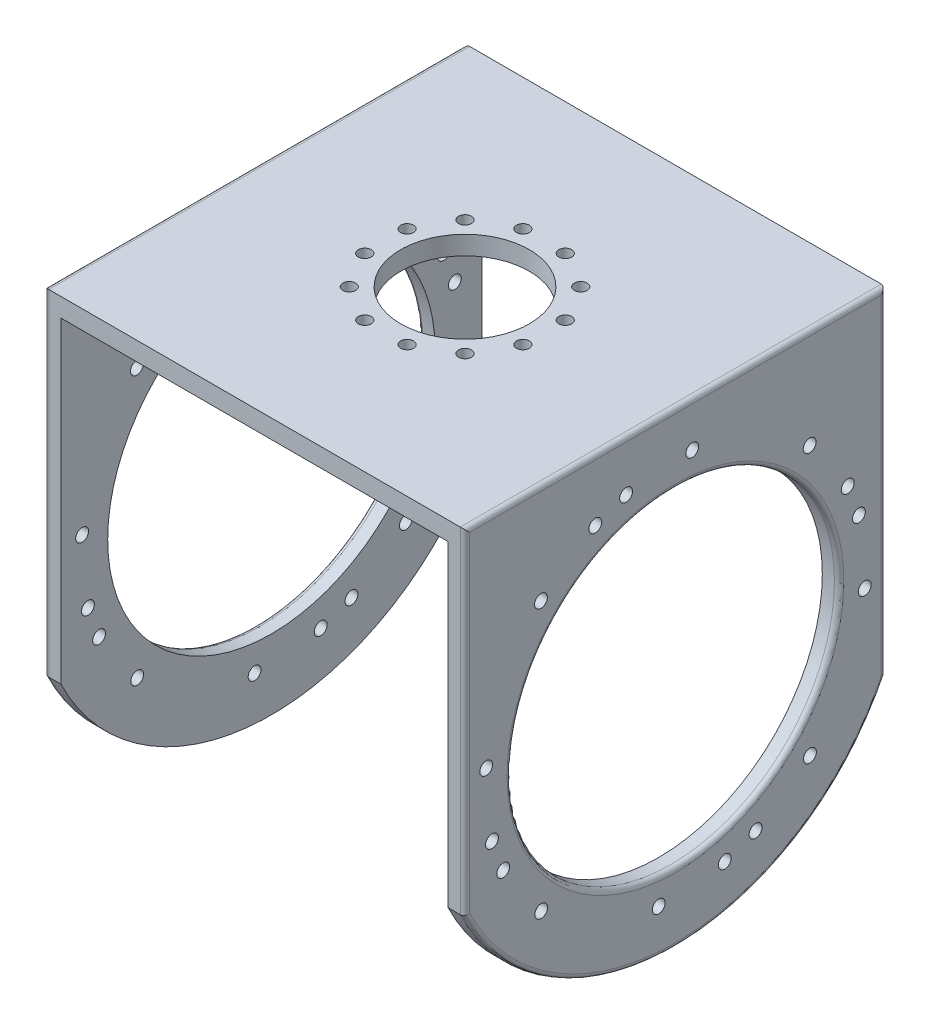
SolidWorks part; units mm, degrees
material "6061 合金"
ref_plane "前视基准面" through (0, 0, 0) normal (0, 0, 1) x (1, 0, 0)
ref_plane "上视基准面" through (0, 0, 0) normal (0, 1, 0) x (1, 0, 0)
ref_plane "右视基准面" through (0, 0, 0) normal (1, 0, 0) x (0, 0, -1)
other "Configuration Table"
sketch "草图1" plane through (0, 0, 0) normal (0, 0, 1) x (1, 0, 0)
  line L0 (0, 0) -> (0, 218.3382) construction
  line L1 (-90, 200) -> (90, 200)
  line L2 (90, 200) -> (90, 0)
  line L3 (90, 0) -> (82.8, 0)
  line L4 (82.8, 0) -> (82.8, 192)
  line L5 (82.8, 192) -> (-82.8, 192)
  line L6 (-82.8, 0) -> (-82.8, 192)
  line L7 (-90, 0) -> (-82.8, 0)
  line L8 (-90, 200) -> (-90, 0)
  point P11 (0, 192)
  point P14 (0, 200)
  dimension "D1" = 8
  dimension "D2" = 7.2
  dimension "D3" = 200
  dimension "D4" = 90
extrude "凸台-拉伸1" add sketch "草图1" along normal blind 180
sketch "草图2" plane through (0, 200, 0) normal (0, 1, 0) x (1, 0, 0)
  line L0 (-107.1953, -90) -> (124.7074, -90) construction
  line L1 (0, 14.5236) -> (0, -191.0225) construction
  line L2 (90, 0) -> (-90, 0) construction
  line L3 (90, -180) -> (-90, -180) construction
  circle A0 centre (0, -90) radius 27.5
  dimension "D1" = 55
extrude "切除-拉伸1" cut sketch "草图2" against normal blind 180
sketch "草图3" plane through (90, 0, 0) normal (1, 0, 0) x (0, 0, -1)
  line L0 (-202.0275, 100) -> (22.0275, 100) construction
  line L1 (-90, 182.9754) -> (-90, -6.0566) construction
  line L2 (-180, 0) -> (0, 0) construction
  line L3 (-180, 200) -> (0, 200) construction
  line L4 (0, 0) -> (0, 200) construction
  line L5 (-180, 0) -> (-180, 200) construction
  circle A0 centre (-90, 100) radius 70
  dimension "D1" = 140
extrude "切除-拉伸2" cut sketch "草图3" against normal blind 217 contours A0
sketch "草图4" plane through (0, 0, 0) normal (1, 0, 0) x (0, 0, -1)
  line L0 (-90, 200) -> (-90, 143.0513) construction
  line L1 (-62.5, 200) -> (-117.5, 200) construction
  line L2 (-70, 430) -> (60, 66.6573)
  line L3 (60, 66.6573) -> (-90, 66.6573) construction
  line L4 (-90, 66.6573) -> (-90, 700) construction
  line L5 (-70, 700) -> (60, 700)
  line L6 (60, 700) -> (60, 66.6573)
  line L7 (-70, 700) -> (-70, 430)
  circle A0 centre (-90, 100) radius 70 construction
  dimension "D1" = 500
  dimension "D2" = 130
  dimension "D3" = 150
  dimension "D4" = 230
  dimension "D5" = 20
revolve "切除-旋转6" [suppressed] cut sketch "草图4" angle 360 about L4
sketch "草图6" [suppressed] plane through (0, 0, 0) normal (1, 0, 0) x (0, 0, -1)
  line L0 (15.1538, 192) -> (60, 66.6573)
  line L1 (-25.1812, 192) -> (0, 192) construction
  line L2 (60, 66.6573) -> (-90, 66.6573) construction
  line L3 (60, 66.6573) -> (51.5034, 66.6573)
  line L4 (51.5034, 66.6573) -> (6.6571, 192)
  line L5 (-70, 430) -> (60, 66.6573) construction
  line L6 (6.6571, 192) -> (15.1538, 192)
  line L7 (-90, 66.6573) -> (-90, 200) construction
  dimension "D1" = 8
revolve "旋转1" [suppressed] add sketch "草图6" angle 360 about L7
sketch "草图7" [suppressed] plane through (0, 0, 0) normal (0, 0, 1) x (1, 0, 0)
  line L0 (90, 0) -> (90, 200)
  line L1 (90, 200) -> (162.5084, 200)
  line L2 (162.5084, 200) -> (162.5084, -21.519)
  line L3 (162.5084, -21.519) -> (-191.6551, -21.519)
  line L4 (-191.6551, -21.519) -> (-191.6551, 200)
  line L5 (-191.6551, 200) -> (-90, 200)
  line L6 (-90, 200) -> (-90, 0)
  line L7 (-90, 0) -> (-82.8, 0)
  line L10 (-35.2505, 192) -> (35.2505, 192)
  line L12 (82.8, 0) -> (90, 0)
  line L14 (35.2505, 192) -> (-35.2505, 192) construction
  line L15 (82.8, 0) -> (82.8, 120.3462)
  line L16 (82.8, 120.3462) -> (35.2505, 192)
  line L17 (-82.8, 0) -> (-82.8, 120.3462)
  line L18 (-82.8, 120.3462) -> (-35.2505, 192)
  line L19 (0, 0) -> (0, 120.3462) construction
  line L21 (35.2505, 192) -> (82.8, 192) construction
  line L22 (-82.8, 0) -> (-82.8, 120.3462) construction
  line L23 (-141.5034, 66.6573) -> (141.5034, 66.6573) construction
  line L24 (-35.2505, 192) -> (35.2505, 192) construction
  dimension "D1" = 53.6889
  dimension "D2" = 35.2505
extrude "切除-拉伸3" [suppressed] cut sketch "草图7" against normal through all both and the other way through all
sketch "草图8" [suppressed] plane through (-90, 0, 0) normal (-1, 0, 0) x (0, 0, 1)
  line L0 (0, 0) -> (0, 200)
  line L1 (0, 200) -> (180, 200)
  line L2 (180, 200) -> (180, 0)
  line L3 (180, 106.4129) -> (180, 0) construction
  line L4 (180, 0) -> (231.7354, 0)
  line L5 (231.7354, 0) -> (231.7354, 213.4055)
  line L6 (231.7354, 213.4055) -> (-43.5189, 213.4055)
  line L7 (-43.5189, 213.4055) -> (-43.5189, 0)
  line L8 (-43.5189, 0) -> (0, 0)
extrude "切除-拉伸4" [suppressed] cut sketch "草图8" against normal through all both
sketch "草图9" plane through (90, 0, 0) normal (1, 0, 0) x (0, 0, -1)
  line L3 (0, 56.411) -> (0, 0)
  line L4 (-180, 200) -> (-180, 0)
  line L5 (-180, 0) -> (0, 0)
  line L6 (0, 0) -> (0, 200)
  line L7 (0, 200) -> (-180, 200)
  line L8 (-180, 56.411) -> (-180, 0)
  line L9 (-180, 0) -> (0, 0)
  line L11 (0, 200) -> (-180, 200) construction
  circle A0 centre (-90, 100) radius 70 construction
  circle A1 centre (-90, 100) radius 70 construction
  arc A3 (-180, 56.411) -> (0, 56.411) centre (-90, 100) ccw
  line M11 (-180, 200) -> (-180, 0)
  line M12 (-180, 0) -> (0, 0)
  line M13 (0, 0) -> (0, 200)
  dimension "D1" = 0
extrude "切除-拉伸5" cut sketch "草图9" against normal through all both contours A3 L9 M13 | A3 M11 M12
fillet "圆角1" [suppressed] radius 2
fillet "圆角2" radius 2 10 edges at (90, 200, 90) (90, 128.2055, 0) (90, 0, 90) (90, 128.2055, 180) (90, 170, 90) (-90, 128.2055, 0) (-90, 200, 90) (-90, 128.2055, 180) (-90, 0, 90) (-90, 170, 90)
sketch "草图10" plane through (90, 0, 0) normal (1, 0, 0) x (0, 0, -1)
  arc A0 (-173.1989, 108.2258) -> (-168.6673, 106.1128) centre (-170.9331, 107.1693) ccw construction
  arc A1 (-170.7244, 79.9423) -> (-166.1928, 77.8292) centre (-168.4586, 78.8857) ccw construction
  arc A2 (-165.9405, 66.7988) -> (-161.409, 64.6857) centre (-163.6748, 65.7423) ccw construction
  arc A3 (-149.6558, 43.5418) -> (-145.1242, 41.4287) centre (-147.39, 42.4852) ccw construction
  arc A4 (-99.4351, 20.1235) -> (-94.9035, 18.0104) centre (-97.1693, 19.0669) ccw construction
  arc A5 (-71.1515, 22.598) -> (-66.62, 20.4849) centre (-68.8857, 21.5414) ccw construction
  arc A6 (-58.008, 27.3818) -> (-53.4765, 25.2687) centre (-55.7423, 26.3252) ccw construction
  arc A7 (-34.751, 43.6665) -> (-30.2194, 41.5535) centre (-32.4852, 42.61) ccw construction
  arc A8 (-11.3327, 93.8872) -> (-6.8011, 91.7742) centre (-9.0669, 92.8307) ccw construction
  arc A9 (-13.8072, 122.1708) -> (-9.2756, 120.0577) centre (-11.5414, 121.1143) ccw construction
  arc A10 (-18.591, 135.3143) -> (-14.0595, 133.2012) centre (-16.3252, 134.2577) ccw construction
  arc A11 (-34.8758, 158.5713) -> (-30.3442, 156.4582) centre (-32.61, 157.5148) ccw construction
  arc A12 (-85.0965, 181.9896) -> (-80.5649, 179.8765) centre (-82.8307, 180.9331) ccw construction
  arc A13 (-108.8485, 177.402) -> (-113.38, 179.5151) centre (-111.1143, 178.4586) ccw construction
  arc A14 (-121.992, 172.6182) -> (-126.5235, 174.7313) centre (-124.2577, 173.6748) ccw construction
  arc A15 (-145.249, 156.3335) -> (-149.7806, 158.4465) centre (-147.5148, 157.39) ccw construction
  arc A16 (-173.1989, 108.2258) -> (-168.6673, 106.1128) centre (-170.9331, 107.1693) ccw construction
  arc A17 (-170.7244, 79.9423) -> (-166.1928, 77.8292) centre (-168.4586, 78.8857) ccw construction
  arc A18 (-165.9405, 66.7988) -> (-161.409, 64.6857) centre (-163.6748, 65.7423) ccw construction
  arc A19 (-149.6558, 43.5418) -> (-145.1242, 41.4287) centre (-147.39, 42.4852) ccw construction
  arc A20 (-99.4351, 20.1235) -> (-94.9035, 18.0104) centre (-97.1693, 19.0669) ccw construction
  arc A21 (-71.1515, 22.598) -> (-66.62, 20.4849) centre (-68.8857, 21.5414) ccw construction
  arc A22 (-58.008, 27.3818) -> (-53.4765, 25.2687) centre (-55.7423, 26.3252) ccw construction
  arc A23 (-34.751, 43.6665) -> (-30.2194, 41.5535) centre (-32.4852, 42.61) ccw construction
  arc A24 (-11.3327, 93.8872) -> (-6.8011, 91.7742) centre (-9.0669, 92.8307) ccw construction
  arc A25 (-13.8072, 122.1708) -> (-9.2756, 120.0577) centre (-11.5414, 121.1143) ccw construction
  arc A26 (-18.591, 135.3143) -> (-14.0595, 133.2012) centre (-16.3252, 134.2577) ccw construction
  arc A27 (-34.8758, 158.5713) -> (-30.3442, 156.4582) centre (-32.61, 157.5148) ccw construction
  arc A28 (-85.0965, 181.9896) -> (-80.5649, 179.8765) centre (-82.8307, 180.9331) ccw construction
  arc A29 (-108.8485, 177.402) -> (-113.38, 179.5151) centre (-111.1143, 178.4586) ccw construction
  arc A30 (-121.992, 172.6182) -> (-126.5235, 174.7313) centre (-124.2577, 173.6748) ccw construction
  arc A31 (-145.249, 156.3335) -> (-149.7806, 158.4465) centre (-147.5148, 157.39) ccw construction
  circle A32 centre (-32.61, 157.5148) radius 2.75
  circle A33 centre (-16.3252, 134.2577) radius 2.75
  circle A34 centre (-11.5414, 121.1143) radius 2.75
  circle A35 centre (-9.0669, 92.8307) radius 2.75
  circle A36 centre (-32.4852, 42.61) radius 2.75
  circle A37 centre (-55.7423, 26.3252) radius 2.75
  circle A38 centre (-68.8857, 21.5414) radius 2.75
  circle A39 centre (-97.1693, 19.0669) radius 2.75
  circle A40 centre (-147.39, 42.4852) radius 2.75
  circle A41 centre (-163.6748, 65.7423) radius 2.75
  circle A42 centre (-168.4586, 78.8857) radius 2.75
  circle A43 centre (-170.9331, 107.1693) radius 2.75
  circle A44 centre (-147.5148, 157.39) radius 2.75
  circle A45 centre (-124.2577, 173.6748) radius 2.75
  circle A46 centre (-111.1143, 178.4586) radius 2.75
  circle A47 centre (-82.8307, 180.9331) radius 2.75
  dimension "D1" = 5.5
extrude "切除-拉伸6" cut sketch "草图10" against normal through all both and the other way through all
sketch "草图11" plane through (0, 192, 0) normal (0, -1, 0) x (1, 0, 0)
  line L0 (0, 90) -> (0, 156.7057) construction
  line L1 (0, 90) -> (16.0765, 149.9982) construction
  circle A0 centre (9.0587, 123.8074) radius 2.75
  circle A1 centre (24.7487, 114.7487) radius 2.75
  circle A2 centre (33.8074, 99.0587) radius 2.75
  circle A3 centre (33.8074, 80.9413) radius 2.75
  circle A4 centre (24.7487, 65.2513) radius 2.75
  circle A5 centre (9.0587, 56.1926) radius 2.75
  circle A6 centre (-9.0587, 56.1926) radius 2.75
  circle A7 centre (-24.7487, 65.2513) radius 2.75
  circle A8 centre (-33.8074, 80.9413) radius 2.75
  circle A9 centre (-33.8074, 99.0587) radius 2.75
  circle A10 centre (-24.7487, 114.7487) radius 2.75
  circle A11 centre (-9.0587, 123.8074) radius 2.75
  point P31 (0, 90)
  dimension "D1" = 5.5
  dimension "D2" = 35
  dimension "D3" = 15
  dimension "D4" = 12
extrude "切除-拉伸7" cut sketch "草图11" against normal blind 29
